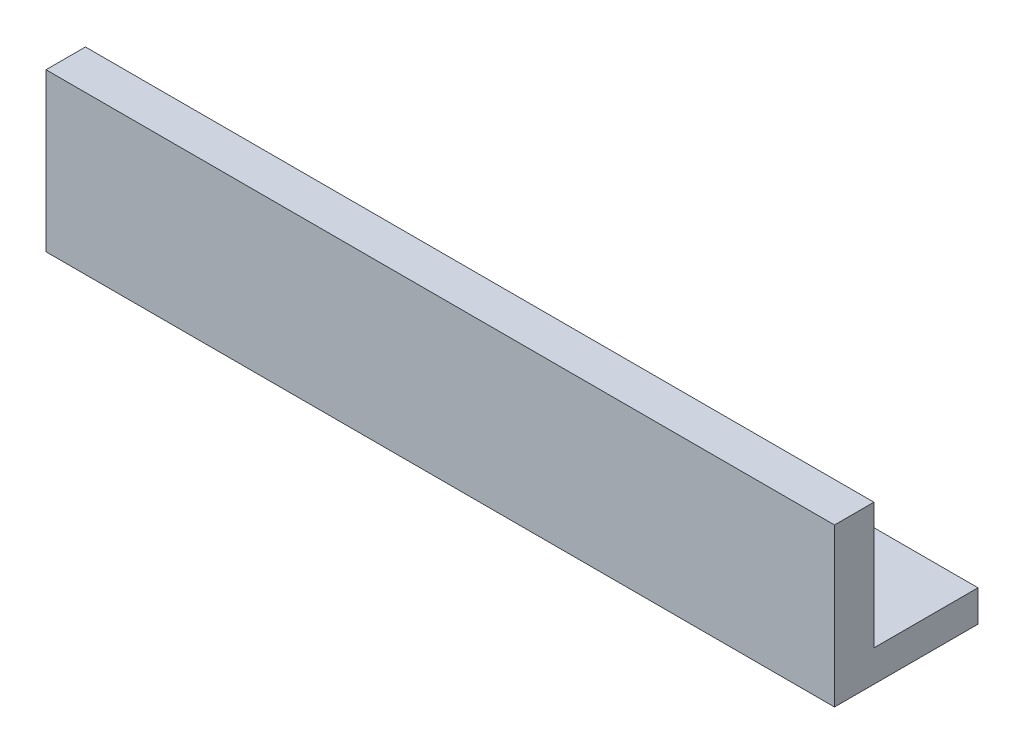
SolidWorks part; units mm, degrees
ref_plane "前视基准面" through (0, 0, 0) normal (0, 0, 1) x (1, 0, 0)
ref_plane "上视基准面" through (0, 0, 0) normal (0, 1, 0) x (1, 0, 0)
ref_plane "右视基准面" through (0, 0, 0) normal (1, 0, 0) x (0, 0, -1)
sketch "Sketch1" plane through (0, 0, 0) normal (0, 1, 0) x (1, 0, 0)
  line L1 (0, 0) -> (50, 0)
  line L2 (0, 0) -> (0, 8.6)
  line L3 (0, 8.6) -> (50, 8.6)
  line L4 (50, 0) -> (50, 8.6)
  dimension "D1" = 8.6
  dimension "D2" = 50
extrude "Boss-Extrude2" add sketch "Sketch1" along normal blind 2
sketch "Sketch3" plane through (0, 2, 0) normal (0, 1, 0) x (1, 0, 0)
  line L0 (50, 0) -> (50, 8.6) construction
  line L1 (0, 0) -> (50, 0)
  line L2 (0, 0) -> (0, 2)
  line L3 (0, 2) -> (50, 2)
  line L4 (50, 0) -> (50, 2)
  dimension "D1" = 2
extrude "Boss-Extrude3" add sketch "Sketch3" along normal blind 8
sketch "Sketch4" plane through (0, 2, 0) normal (0, 1, 0) x (1, 0, 0)
  line L0 (50, 8.6) -> (0, 8.6) construction
  line L1 (12.5, 8.6) -> (37.5, 8.6)
  line L2 (12.5, 8.6) -> (12.5, 2)
  line L3 (12.5, 2) -> (37.5, 2)
  line L4 (37.5, 8.6) -> (37.5, 2)
  line L5 (50, 2) -> (0, 2) construction
  line L6 (0, 8.6) -> (0, 2) construction
  line L7 (50, 2) -> (50, 8.6) construction
  dimension "D1" = 12.5
  dimension "D2" = 12.5
extrude "Cut-Extrude1" cut sketch "Sketch4" against normal blind 8
sketch "Sketch5" plane through (0, 0, -2) normal (0, 0, -1) x (-1, 0, 0)
  line L1 (-37.5, 0) -> (-12.5, 0)
  line L2 (-37.5, 0) -> (-37.5, 2)
  line L3 (-37.5, 2) -> (-12.5, 2)
  line L4 (-12.5, 0) -> (-12.5, 2)
extrude "Cut-Extrude2" cut sketch "Sketch5" against normal blind 2
sketch "Sketch6" plane through (0, 2, 0) normal (0, 1, 0) x (1, 0, 0)
  circle A0 centre (43.75, 5.3) radius 1.8
  circle A1 centre (6.25, 5.3) radius 1.8
  dimension "D1" = 3.6
  dimension "D2" = 3.6
extrude "Cut-Extrude3" cut sketch "Sketch6" against normal blind 2
sketch "Sketch7" plane through (0, 0, 0) normal (0, 0, 1) x (1, 0, 0)
  line L0 (12.5, 0) -> (0, 0)
  line L1 (0, 0) -> (0, 10)
  line L2 (0, 10) -> (50, 10)
  line L3 (50, 10) -> (50, 0)
  line L4 (50, 0) -> (37.5, 0)
  line L5 (37.5, 0) -> (37.5, 2)
  line L6 (37.5, 2) -> (12.5, 2)
  line L7 (12.5, 2) -> (12.5, 0)
extrude "Boss-Extrude4" add sketch "Sketch7" along normal blind 0.5
sketch "Sketch8" plane through (0, 0, 0.5) normal (0, 0, 1) x (1, 0, 0)
  line L1 (12.5, 0) -> (37.5, 0)
  line L2 (12.5, 0) -> (12.5, 2)
  line L3 (12.5, 2) -> (37.5, 2)
  line L4 (37.5, 0) -> (37.5, 2)
extrude "Boss-Extrude5" add sketch "Sketch8" against normal blind 2.5
